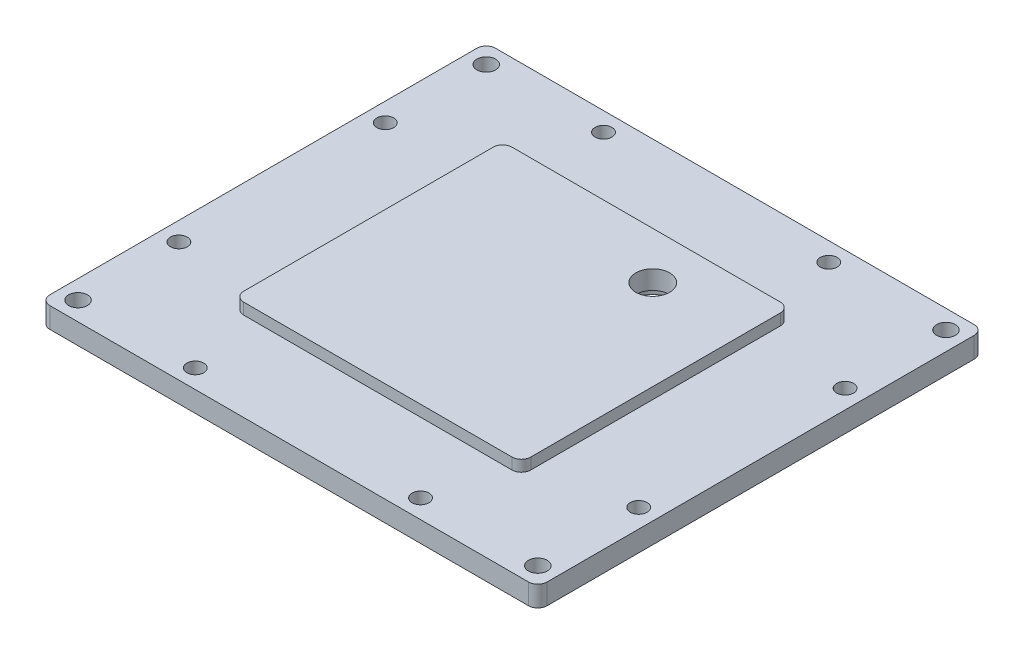
SolidWorks part; units mm, degrees
ref_plane "Front Plane" through (0, 0, 0) normal (0, 0, 1) x (1, 0, 0)
ref_plane "Top Plane" through (0, 0, 0) normal (0, 1, 0) x (1, 0, 0)
ref_plane "Right Plane" through (0, 0, 0) normal (1, 0, 0) x (0, 0, -1)
sketch "Sketch1" plane through (0, 0, 0) normal (0, 1, 0) x (1, 0, 0)
  line L1 (-265, -237.5) -> (265, -237.5)
  line L2 (-265, -237.5) -> (-265, 237.5)
  line L3 (-265, 237.5) -> (265, 237.5)
  line L4 (265, -237.5) -> (265, 237.5)
  line L5 (-265, -237.5) -> (265, 237.5) construction
  line L6 (-265, 237.5) -> (265, -237.5) construction
  point P0 (0, 0)
  dimension "D1" = 530
  dimension "D2" = 475
extrude "Boss-Extrude1" add sketch "Sketch1" along normal mid plane 22
sketch "Sketch2" plane through (0, 11, 0) normal (0, 1, 0) x (1, 0, 0)
  line L1 (-153, -143) -> (153, -143)
  line L2 (-153, -143) -> (-153, 143)
  line L3 (-153, 143) -> (153, 143)
  line L4 (153, -143) -> (153, 143)
  line L5 (-153, -143) -> (153, 143) construction
  line L6 (-153, 143) -> (153, -143) construction
  point P0 (0, 0)
  dimension "D1" = 306
  dimension "D2" = 286
extrude "Boss-Extrude2" add sketch "Sketch2" along normal blind 12
sketch "Sketch3" plane through (0, 11, 0) normal (0, 1, 0) x (1, 0, 0)
  line L0 (-245, 110) -> (-245, 217.5) construction
  line L1 (-245, 217.5) -> (-120, 217.5) construction
  line L2 (-265, 237.5) -> (-265, -237.5) construction
  line L3 (265, 237.5) -> (-265, 237.5) construction
  line L4 (-82.9386, 0) -> (0, 0) construction
  line L5 (0, 0) -> (0, 89.0153) construction
  circle A0 centre (-245, 217.5) radius 10
  circle A1 centre (-120, 217.5) radius 9
  circle A2 centre (-245, 110) radius 9
  circle A3 centre (120, 217.5) radius 9
  circle A4 centre (245, 217.5) radius 10
  circle A5 centre (245, 110) radius 9
  circle A6 centre (245, -110) radius 9
  circle A7 centre (245, -217.5) radius 10
  circle A8 centre (120, -217.5) radius 9
  circle A9 centre (-120, -217.5) radius 9
  circle A10 centre (-245, -110) radius 9
  circle A11 centre (-245, -217.5) radius 10
  dimension "D5" = 20
  dimension "D6" = 18
  dimension "D7" = 18
  dimension "D1" = 125
  dimension "D2" = 107.5
  dimension "D3" = 20
  dimension "D4" = 20
extrude "Cut-Extrude1" cut sketch "Sketch3" against normal through all
sketch "Sketch4" plane through (0, 23, 0) normal (0, 1, 0) x (1, 0, 0)
  circle A0 centre (57, 93) radius 18
  dimension "D1" = 36
  dimension "D2" = 93
  dimension "D3" = 57
extrude "Cut-Extrude2" cut sketch "Sketch4" against normal through all
sketch "Sketch5" plane through (0, -11, 0) normal (0, -1, 0) x (1, 0, 0)
  circle A0 centre (57, -93) radius 32.5
  dimension "D1" = 65
extrude "Cut-Extrude3" cut sketch "Sketch5" against normal blind 14
fillet "Fillet1" radius 10 8 edges at (265, 0, -237.5) (265, 0, 237.5) (-265, 0, -237.5) (-265, 0, 237.5) (153, 17, -143) (-153, 17, -143) (-153, 17, 143) (153, 17, 143)
